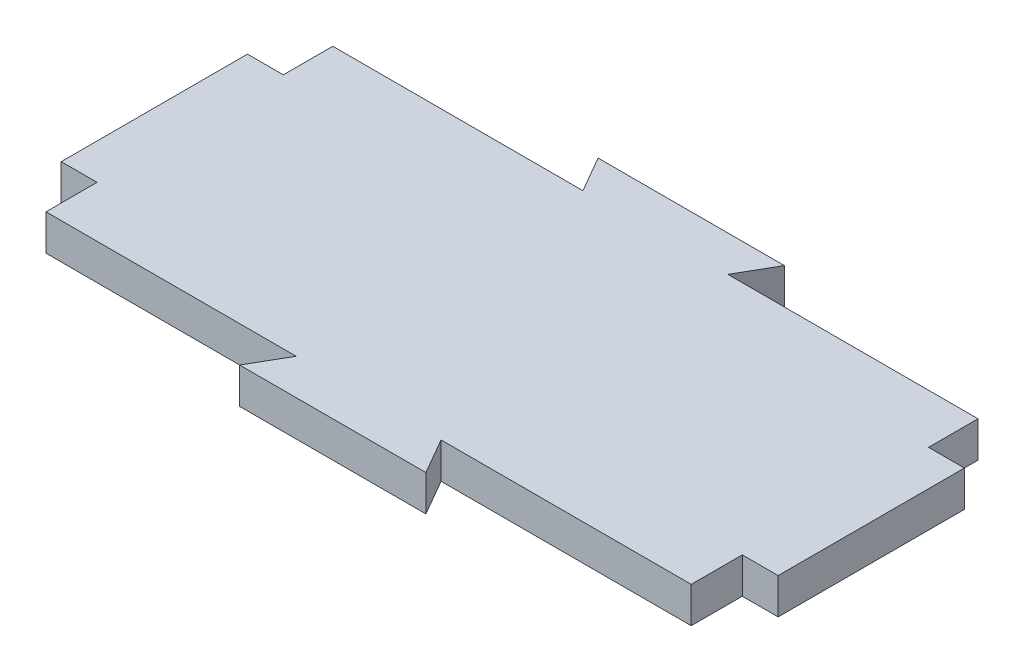
SolidWorks part; units mm, degrees
ref_plane "Front Plane" through (0, 0, 0) normal (1, 0, 0) x (0, 1, 0)
ref_plane "Top Plane" through (0, 0, 0) normal (0, 0, 1) x (0, 1, 0)
ref_plane "Right Plane" through (0, 0, 0) normal (0, 1, 0) x (-1, 0, 0)
sketch "Sketch2" plane through (0, 0, 0) normal (0, 1, 0) x (-1, 0, 0)
  line L1 (-45, -20) -> (45, -20)
  line L2 (-45, -20) -> (-45, 20)
  line L3 (-45, 20) -> (45, 20)
  line L4 (45, -20) -> (45, 20)
  line L5 (-45, -20) -> (45, 20) construction
  line L6 (-45, 20) -> (45, -20) construction
  line L9 (0, 55) -> (0, -55) construction
  line L13 (12.9904, 25) -> (-12.9904, 25)
  line L14 (-12.9904, 25) -> (0, 2.5)
  line L15 (0, 2.5) -> (12.9904, 25)
  line L16 (55, 0) -> (-55, 0) construction
  line L17 (0, -2.5) -> (12.9904, -25)
  line L18 (-12.9904, -25) -> (0, -2.5)
  line L19 (12.9904, -25) -> (-12.9904, -25)
  line L20 (45, -13.1038) -> (50, -13.1038)
  line L21 (-45, 12.877) -> (-50, 12.877)
  line L22 (-45, 12.877) -> (-45, -13.1038)
  line L23 (-45, -13.1038) -> (-50, -13.1038)
  line L24 (-50, 12.877) -> (-50, -13.1038)
  line L25 (50, 12.877) -> (50, -13.1038)
  line L26 (45, 12.877) -> (50, 12.877)
  line L27 (45, 12.877) -> (45, -13.1038)
  circle A2 centre (0, 17.5) radius 7.5
  circle A3 centre (0, -17.5) radius 7.5
  point P0 (0, 0)
  dimension "D6" = 15
  dimension "D1" = 40
  dimension "D2" = 90
  dimension "D3" = 5
  dimension "D7" = 45
  dimension "D8" = 5
extrude "Boss-Extrude1" add sketch "Sketch2" along normal blind 5
